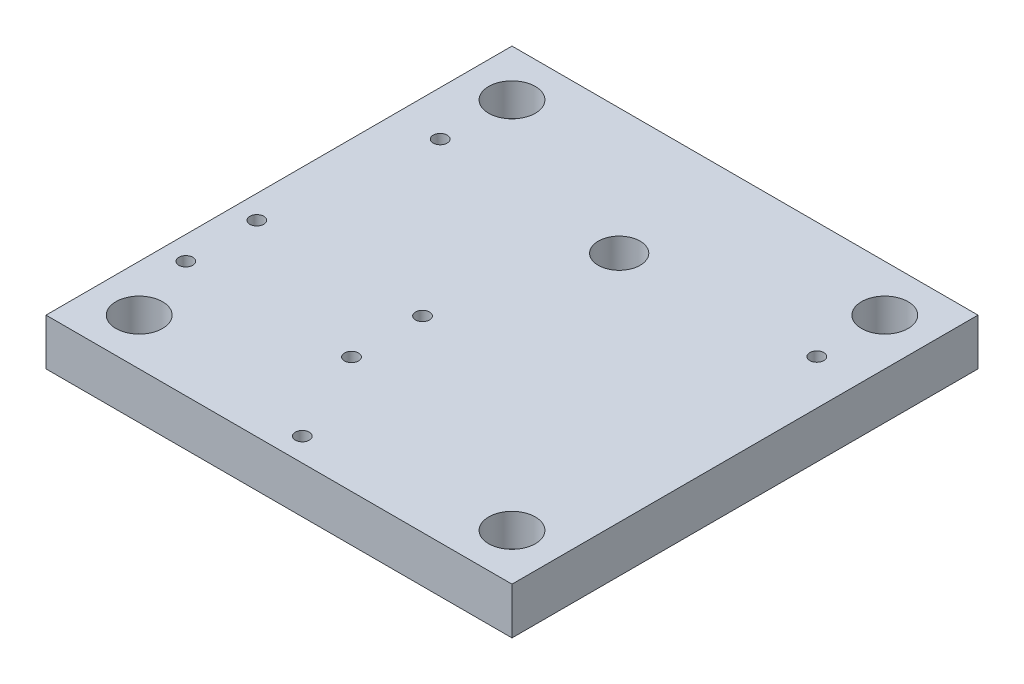
SolidWorks part; units mm, degrees
ref_plane "前视基准面" through (0, 0, 0) normal (0, 0, 1) x (1, 0, 0)
ref_plane "上视基准面" through (0, 0, 0) normal (0, 1, 0) x (1, 0, 0)
ref_plane "右视基准面" through (0, 0, 0) normal (1, 0, 0) x (0, 0, -1)
sketch "草图1" plane through (0, 0, 0) normal (0, 1, 0) x (1, 0, 0)
  line L1 (0, 0) -> (100, 0)
  line L2 (0, 0) -> (0, -100)
  line L3 (0, -100) -> (100, -100)
  line L4 (100, 0) -> (100, -100)
  dimension "D1" = 100
  dimension "D2" = 100
extrude "凸台-拉伸1" add sketch "草图1" along normal blind 10
sketch "草图2" plane through (0, 10, 0) normal (0, 1, 0) x (1, 0, 0)
  line L0 (10, -10) -> (90, -10) construction
  line L1 (90, -10) -> (90, -90) construction
  line L2 (90, -90) -> (10, -90) construction
  line L3 (10, -90) -> (10, -10) construction
  line L4 (50, -10) -> (50, 0) construction
  line L5 (100, 0) -> (0, 0) construction
  line L6 (10, -50) -> (0, -50) construction
  line L7 (0, 0) -> (0, -100) construction
  circle A0 centre (10, -10) radius 5
  circle A1 centre (90, -10) radius 5
  circle A2 centre (10, -90) radius 5
  circle A3 centre (90, -90) radius 5
  dimension "D2" = 10
  dimension "D1" = 80
extrude "切除-拉伸1" cut sketch "草图2" against normal blind 7
sketch "草图3" plane through (0, 10, 0) normal (0, 1, 0) x (1, 0, 0)
  line L0 (50, -95) -> (90.4145, -25) construction
  line L1 (90.4145, -25) -> (9.5855, -25) construction
  line L2 (9.5855, -25) -> (50, -95) construction
  line L3 (0, -100) -> (100, -100) construction
  line L4 (50, -25) -> (50, 0) construction
  line L6 (100, 0) -> (0, 0) construction
  circle A0 centre (50, -95) radius 1.5
  circle A1 centre (90.4145, -25) radius 1.5
  circle A2 centre (9.5855, -25) radius 1.5
  dimension "D3" = 3
  dimension "D1" = 70
  dimension "D2" = 5
extrude "切除-拉伸2" cut sketch "草图3" against normal through all
sketch "草图4" plane through (0, 10, 0) normal (0, 1, 0) x (1, 0, 0)
  line L0 (50, -27) -> (50, -95) construction
  circle A0 centre (50, -27) radius 4.5
  circle A1 centre (90.4145, -25) radius 1.5 construction
  dimension "D2" = 9
  dimension "D1" = 2
extrude "切除-拉伸3" cut sketch "草图4" against normal through all
sketch "草图5" plane through (0, 0, 0) normal (0, -1, 0) x (-1, 0, 0)
  circle A0 centre (-50, -27) radius 6.5
  dimension "D1" = 13
extrude "切除-拉伸4" cut sketch "草图5" against normal blind 3
sketch "草图6" plane through (0, 10, 0) normal (0, 1, 0) x (1, 0, 0)
  line L0 (40.56, -59.76) -> (40.56, -75) construction
  line L1 (40.56, -75) -> (5, -75) construction
  line L2 (5, -75) -> (5, -59.76) construction
  line L3 (5, -59.76) -> (40.56, -59.76) construction
  line L4 (0, 0) -> (0, -100) construction
  line L5 (0, -100) -> (100, -100) construction
  circle A0 centre (40.56, -59.76) radius 1.5
  circle A1 centre (40.56, -75) radius 1.5
  circle A2 centre (5, -59.76) radius 1.5
  circle A3 centre (5, -75) radius 1.5
  dimension "D3" = 3
  dimension "D1" = 35.56
  dimension "D2" = 15.24
  dimension "D4" = 5
  dimension "D5" = 25
extrude "切除-拉伸5" cut sketch "草图6" against normal through all
sketch "草图7" plane through (0, 0, 0) normal (0, -1, 0) x (-1, 0, 0)
  line L0 (-50, -27) -> (49950, -27) construction
  circle A0 centre (-65, -27) radius 1.4
  circle A1 centre (-35, -27) radius 1.4
  circle A2 centre (-50, -27) radius 4.5 construction
  dimension "D1" = 2.8
  dimension "D2" = 15
  dimension "D3" = 15
extrude "切除-拉伸6" cut sketch "草图7" against normal blind 5
sketch "草图8" plane through (0, 0, 0) normal (0, -1, 0) x (1, 0, 0)
  line L0 (65, 27) -> (65, 50027) construction
  line L1 (50, 27) -> (50, 50027) construction
  dimension "D1" = 15
